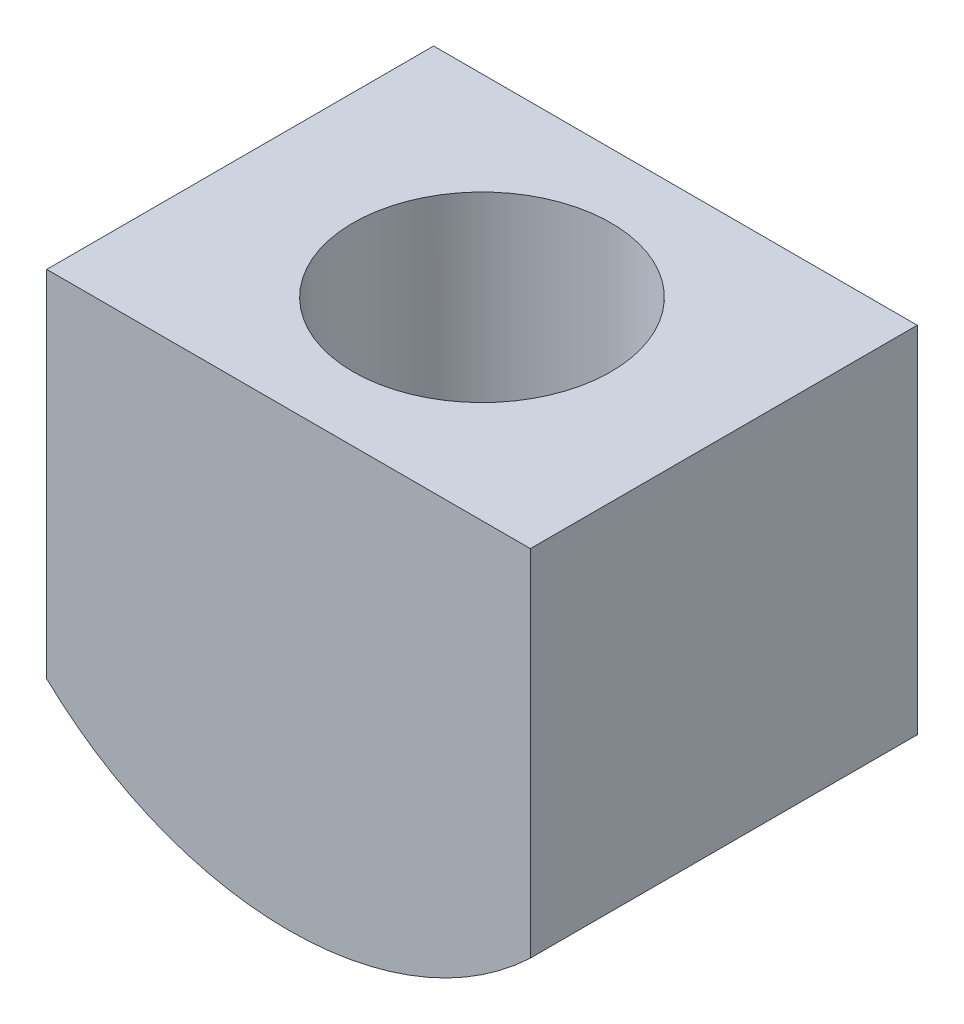
SolidWorks part; units mm, degrees
ref_plane "Płaszczyzna przednia" through (0, 0, 0) normal (0, 0, 1) x (1, 0, 0)
ref_plane "Płaszczyzna górna" through (0, 0, 0) normal (0, 1, 0) x (1, 0, 0)
ref_plane "Płaszczyzna prawa" through (0, 0, 0) normal (1, 0, 0) x (0, 0, -1)
sketch "Szkic1" plane through (0, 0, 0) normal (0, 0, 1) x (1, 0, 0)
  line L0 (0, 0) -> (15, 0)
  line L1 (15, 0) -> (15, -11)
  line L2 (0, 0) -> (0, -11)
  arc A0 (15, -11) -> (0, -11) centre (7.5, -3.125) cw
  dimension "D1" = 15
  dimension "D2" = 11
  dimension "D3" = 11
extrude "Dodanie-wyciągnięcie1" add sketch "Szkic1" along normal blind 12 contours L2 A0 L1 L0
sketch "Szkic2" plane through (0, 0, 0) normal (0, 1, 0) x (1, 0, 0)
  line L0 (0, 0) -> (15, 0) construction
  line L1 (0, -12) -> (0, 0) construction
  circle A0 centre (7.5, -6) radius 4
  point P4 (0, 0)
  point P6 (0, 0)
  dimension "D3" = 8
  dimension "D1" = 6
  dimension "D2" = 7.5
extrude "Wytnij-wyciągnięcie1" cut sketch "Szkic2" against normal blind 21
